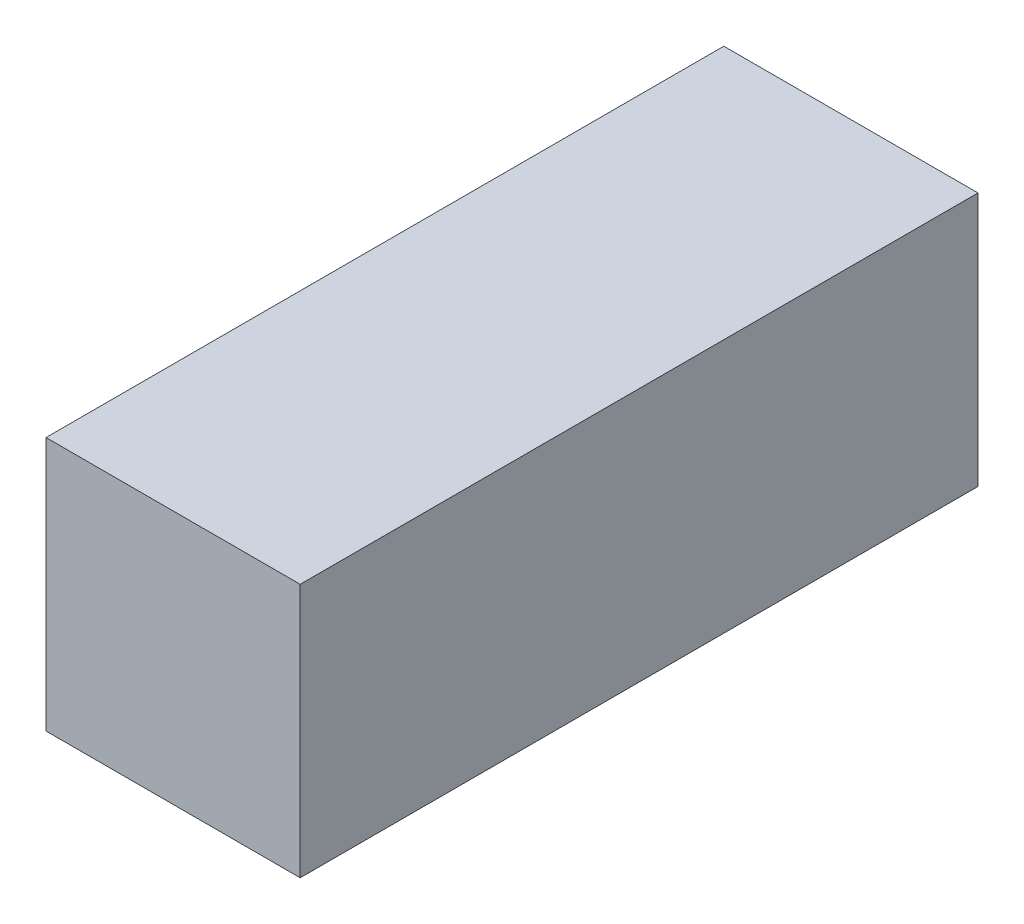
SolidWorks part; units mm, degrees
ref_plane "Front Plane" through (0, 0, 0) normal (0, 0, 1) x (1, 0, 0)
ref_plane "Top Plane" through (0, 0, 0) normal (0, 1, 0) x (1, 0, 0)
ref_plane "Right Plane" through (0, 0, 0) normal (1, 0, 0) x (0, 0, -1)
sketch "Sketch1" plane through (0, 0, 0) normal (0, 0, 1) x (1, 0, 0)
  line L1 (-1.5, 1.5) -> (1.5, 1.5)
  line L2 (-1.5, 1.5) -> (-1.5, -1.5)
  line L3 (-1.5, -1.5) -> (1.5, -1.5)
  line L4 (1.5, 1.5) -> (1.5, -1.5)
  line L5 (-1.5, 1.5) -> (1.5, -1.5) construction
  line L6 (-1.5, -1.5) -> (1.5, 1.5) construction
  point P0 (0, 0)
extrude "Boss-Extrude1" add sketch "Sketch1" along normal blind 8
